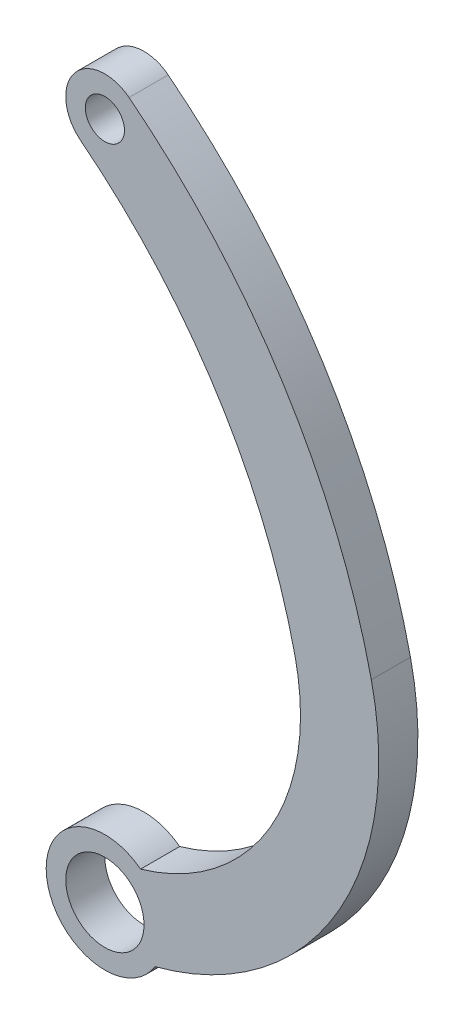
SolidWorks part; units mm, degrees
ref_plane "前视基准面" through (0, 0, 0) normal (0, 0, 1) x (1, 0, 0)
ref_plane "上视基准面" through (0, 0, 0) normal (0, 1, 0) x (1, 0, 0)
ref_plane "右视基准面" through (0, 0, 0) normal (1, 0, 0) x (0, 0, -1)
other "Configuration Table"
sketch "草图1" plane through (0, 0, 0) normal (0, 0, 1) x (1, 0, 0)
  line L0 (0, -52) -> (0, 52) construction
  arc A0 (0, 52) -> (35, -3.3453) centre (-60.568, -25.0423) cw construction
  arc A1 (0, -52) -> (35, -3.3453) centre (-4.0073, -12.2012) ccw construction
  arc A2 (0.6011, -57.9698) -> (40.8511, -2.0169) centre (-4.0073, -12.2012) ccw
  arc A3 (3.7082, 56.7169) -> (40.8511, -2.0169) centre (-60.568, -25.0423) cw
  arc A4 (-0.6011, -46.0302) -> (29.1489, -4.6737) centre (-4.0073, -12.2012) ccw
  arc A5 (-3.7082, 47.2831) -> (29.1489, -4.6737) centre (-60.568, -25.0423) cw
  arc A6 (0.6011, -57.9698) -> (-0.6011, -46.0302) centre (0, -52) cw
  arc A7 (3.7082, 56.7169) -> (-3.7082, 47.2831) centre (0, 52) ccw
  point P4 (0, 0)
  dimension "D2" = 40
  dimension "D3" = 98
  dimension "D1" = 104
  dimension "D4" = 35
  dimension "D5" = 6
  dimension "D6" = 6
extrude "凸台-拉伸1" add sketch "草图1" along normal blind 6
sketch "草图2" plane through (0, 0, 6) normal (0, 0, 1) x (1, 0, 0)
  circle A0 centre (0, -52) radius 9
  dimension "D1" = 18
extrude "凸台-拉伸2" add sketch "草图2" against normal up to surface (6 mm away) up to face at (15.1267, -2.223, 0)
sketch "草图3" plane through (0, 0, 6) normal (0, 0, 1) x (1, 0, 0)
  circle A0 centre (0, -52) radius 6
  circle A2 centre (0, 52) radius 3
  dimension "D1" = 12
  dimension "D2" = 6
extrude "切除-拉伸1" cut sketch "草图3" against normal up to surface (6 mm away) up to face at (15.26, -1.4656, 0)
